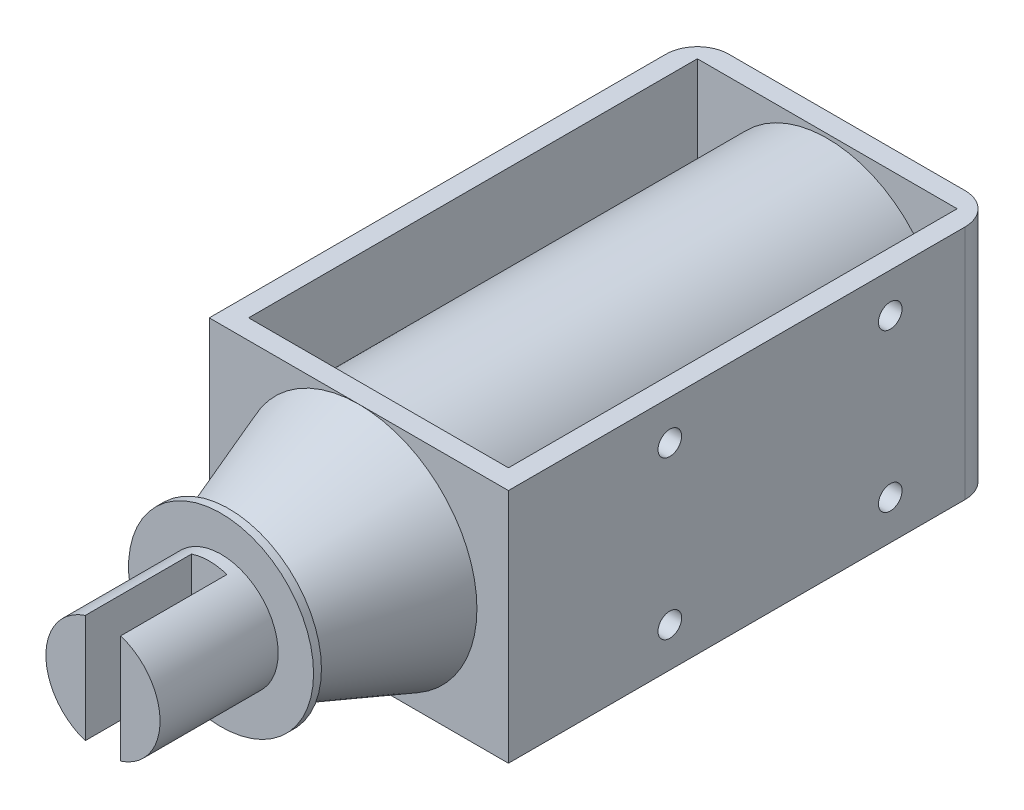
SolidWorks part; units mm, degrees
ref_plane "Front Plane" through (0, 0, 0) normal (0, 0, 1) x (1, 0, 0)
ref_plane "Top Plane" through (0, 0, 0) normal (0, 1, 0) x (1, 0, 0)
ref_plane "Right Plane" through (0, 0, 0) normal (1, 0, 0) x (0, 0, -1)
sketch "Sketch1" plane through (0, 0, 0) normal (0, 1, 0) x (1, 0, 0)
  line L1 (-19, -31) -> (19, -31)
  line L2 (-19, -31) -> (-19, 31)
  line L3 (-19, 31) -> (19, 31)
  line L4 (19, -31) -> (19, 31)
  line L5 (-19, -31) -> (19, 31) construction
  line L6 (-19, 31) -> (19, -31) construction
  point P0 (0, 0)
  dimension "D1" = 38
  dimension "D2" = 62
extrude "Boss-Extrude1" add sketch "Sketch1" along normal blind 30
sketch "Sketch2" plane through (0, 30, 0) normal (0, 1, 0) x (1, 0, 0)
  line L0 (19, 31) -> (-19, 31) construction
  line L1 (-16.5, -28.5) -> (16.5, -28.5)
  line L2 (-16.5, -28.5) -> (-16.5, 28.5)
  line L3 (-16.5, 28.5) -> (16.5, 28.5)
  line L4 (16.5, -28.5) -> (16.5, 28.5)
  line L5 (-16.5, -28.5) -> (16.5, 28.5) construction
  line L6 (-16.5, 28.5) -> (16.5, -28.5) construction
  line L7 (19, -31) -> (19, 31) construction
  point P0 (0, 0)
  dimension "D1" = 2.5
  dimension "D2" = 2.5
extrude "Cut-Extrude1" cut sketch "Sketch2" against normal up to surface (30 mm away) up to face at (0, 0, 0)
fillet "Fillet1" radius 4 2 edges at (-19, 15, -31) (19, 15, -31)
sketch "Sketch3" plane through (19, 0, 0) normal (1, 0, 0) x (0, 0, -1)
  line L0 (31, 30) -> (31, 0) construction
  line L2 (-31, 0) -> (27, 0) construction
  circle A0 centre (17.5, 25) radius 1.5
  circle A1 centre (17.5, 5) radius 1.5
  circle A2 centre (-10.5, 25) radius 1.5
  circle A3 centre (-10.5, 5) radius 1.5
  dimension "D1" = 3
  dimension "D2" = 3
  dimension "D5" = 5
  dimension "D6" = 3
  dimension "D7" = 3
  dimension "D3" = 13.5
  dimension "D4" = 20
  dimension "D8" = 28
extrude "Cut-Extrude2" cut sketch "Sketch3" against normal up to surface (2.5 mm away) up to face at (16.5, 15, 0)
sketch "Sketch4" plane through (0, 0, -28.5) normal (0, 0, 1) x (1, 0, 0)
  line L0 (-19, 30) -> (19, 30) construction
  line L1 (19, 30) -> (19, 0) construction
  circle A0 centre (0, 15) radius 14.5
  dimension "D3" = 29
  dimension "D1" = 15
  dimension "D2" = 19
extrude "Boss-Extrude2" add sketch "Sketch4" along normal up to surface (57 mm away) up to face at (0, 15, 28.5)
sketch "Sketch5" plane through (0, 0, -31) normal (0, 0, -1) x (-1, 0, 0)
  line L0 (-15, 30) -> (15, 30) construction
  line L1 (19, 30) -> (19, 0) construction
  circle A0 centre (0, 15) radius 4.25
  dimension "D1" = 8.5
  dimension "D2" = 15
  dimension "D3" = 19
extrude "Boss-Extrude3" add sketch "Sketch5" along normal blind 0.5
sketch "Sketch6" plane through (0, 0, -31.5) normal (0, 0, -1) x (-1, 0, 0)
  line L1 (0, 19.25) -> (-3.6806, 17.125)
  line L2 (-3.6806, 17.125) -> (-3.6806, 12.875)
  line L3 (-3.6806, 12.875) -> (0, 10.75)
  line L4 (0, 10.75) -> (3.6806, 12.875)
  line L5 (3.6806, 12.875) -> (3.6806, 17.125)
  line L6 (3.6806, 17.125) -> (0, 19.25)
  circle A0 centre (0, 15) radius 3.6806 construction
  dimension "D1" = 4.25
extrude "Boss-Extrude4" add sketch "Sketch6" along normal blind 2.5
sketch "Sketch8" plane through (0, 0, -34) normal (0, 0, -1) x (-1, 0, 0)
  circle A0 centre (0, 15) radius 3.6
  dimension "D1" = 7.2
extrude "Boss-Extrude5" add sketch "Sketch8" along normal blind 4.5
fillet "Fillet2" radius 2 1 edges at (-3.6, 15, -38.5)
sketch "Sketch10" plane through (0, 0, 31) normal (0, 0, 1) x (1, 0, 0)
  line L0 (-19, 30) -> (19, 30) construction
  line L1 (-19, 30) -> (-19, 0) construction
  circle A0 centre (0, 15) radius 7.25
  dimension "D1" = 14.5
  dimension "D2" = 15
  dimension "D3" = 19
extrude "Boss-Extrude6" add sketch "Sketch10" along normal blind 16.5
sketch "Sketch11" plane through (0, 0, 47.5) normal (0, 0, 1) x (1, 0, 0)
  circle A0 centre (0, 15) radius 11.75
  dimension "D1" = 23.5
extrude "Boss-Extrude7" add sketch "Sketch11" along normal blind 1
sketch "Sketch12" plane through (0, 0, 48.5) normal (0, 0, 1) x (1, 0, 0)
  circle A0 centre (0, 15) radius 7.25
  dimension "D1" = 14.5
extrude "Boss-Extrude8" add sketch "Sketch12" along normal blind 15
sketch "Sketch13" plane through (0, 0, 63.5) normal (0, 0, 1) x (1, 0, 0)
  line L1 (-2.25, 7.75) -> (2.25, 7.75)
  line L2 (-2.25, 7.75) -> (-2.25, 22.25)
  line L3 (-2.25, 22.25) -> (2.25, 22.25)
  line L4 (2.25, 7.75) -> (2.25, 22.25)
  line L5 (-2.25, 7.75) -> (2.25, 22.25) construction
  line L6 (-2.25, 22.25) -> (2.25, 7.75) construction
  point P0 (0, 15)
  dimension "D1" = 4.5
  dimension "D2" = 14.5
extrude "Cut-Extrude3" cut sketch "Sketch13" against normal blind 13.5
sketch "Sketch15" plane through (0, 0, 31) normal (0, 0, 1) x (1, 0, 0)
  circle A0 centre (0, 15) radius 15
  dimension "D1" = 30
extrude "Boss-Extrude9" add sketch "Sketch15" along normal up to surface (16.5 mm away) draft 20
